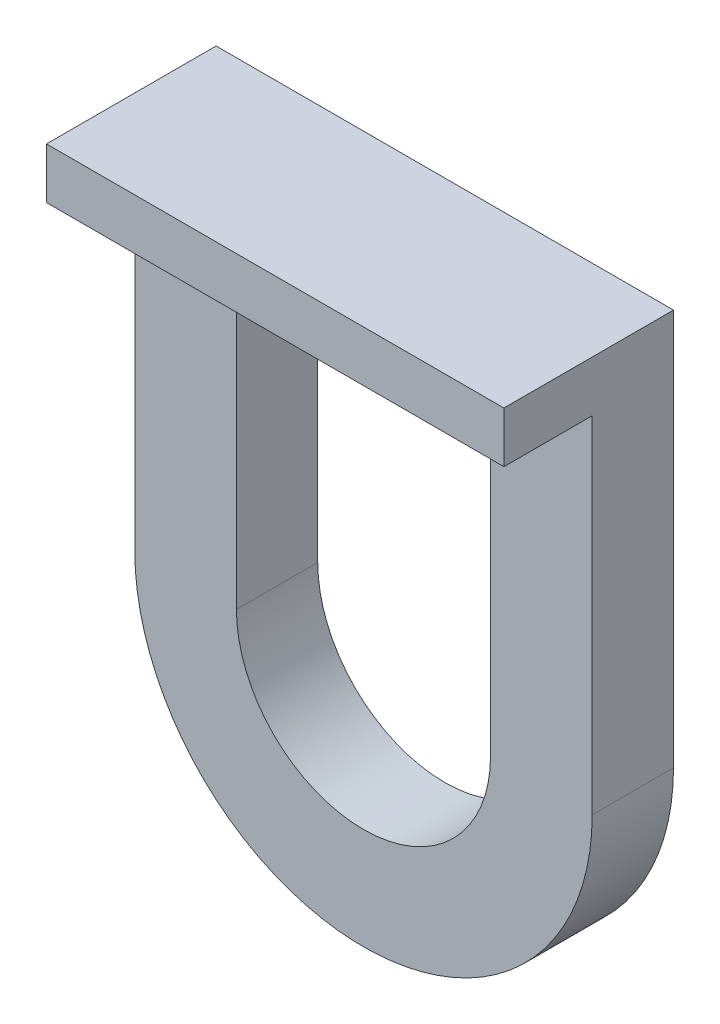
SolidWorks part; units mm, degrees
ref_plane "Front Plane" through (0, 0, 0) normal (0, 0, 1) x (1, 0, 0)
ref_plane "Top Plane" through (0, 0, 0) normal (0, 1, 0) x (1, 0, 0)
ref_plane "Right Plane" through (0, 0, 0) normal (1, 0, 0) x (0, 0, -1)
sketch "Sketch1" plane through (0, 0, 0) normal (0, 0, 1) x (1, 0, 0)
  line L0 (0, 0) -> (0, 34) construction
  line L1 (-12.5, 0) -> (-12.5, 34)
  line L2 (12.5, 0) -> (12.5, 34)
  line L3 (-12.5, 34) -> (-22.5, 34)
  line L4 (-22.5, 34) -> (-22.5, 0)
  line L5 (12.5, 34) -> (22.5, 34)
  line L6 (22.5, 34) -> (22.5, 0)
  circle A0 centre (0, 0) radius 12.5 construction
  arc A1 (-12.5, 0) -> (12.5, 0) centre (0, 0) ccw
  arc A2 (-22.5, 0) -> (22.5, 0) centre (0, 0) ccw
  point P14 (0, 0)
  dimension "D2" = 25
  dimension "D1" = 34
  dimension "D3" = 10
extrude "Boss-Extrude1" add sketch "Sketch1" along normal blind 8
sketch "Sketch2" plane through (0, 34, 0) normal (0, 1, 0) x (1, 0, 0)
  line L0 (-22.5, 0) -> (-22.5, -8.684)
  line L1 (-22.5, -8) -> (-22.5, 0) construction
  line L2 (-22.5, -8.684) -> (-22.5, -16.684)
  line L3 (-22.5, -16.684) -> (22.5, -16.684)
  line L4 (22.5, -16.684) -> (22.5, 0)
  line L5 (22.5, 0) -> (12.5, 0)
  line L6 (12.5, 0) -> (12.5, -8)
  line L7 (12.5, -8) -> (-12.5, -8)
  line L8 (-12.5, -8) -> (-12.5, 0)
  line L9 (-12.5, 0) -> (-22.5, 0)
  dimension "D1" = 8
extrude "Boss-Extrude2" add sketch "Sketch2" along normal blind 5
sketch "Sketch3" plane through (0, 0, 8) normal (0, 0, -1) x (-1, 0, 0)
  line L4 (-12.5, 34) -> (12.5, 34)
  line L5 (12.5, 34) -> (12.5, 39)
  line L6 (12.5, 39) -> (-12.5, 39)
  line L7 (-12.5, 39) -> (-12.5, 34)
  line L8 (-12.5, 34) -> (12.5, 34)
  line L9 (12.5, 34) -> (12.5, 39)
  line L10 (12.5, 39) -> (-12.5, 39)
  line L11 (-12.5, 39) -> (-12.5, 34)
  dimension "D1" = 0
extrude "Boss-Extrude3" add sketch "Sketch3" along normal up to surface (8 mm away) up to face at (0, 15.125, 0)
